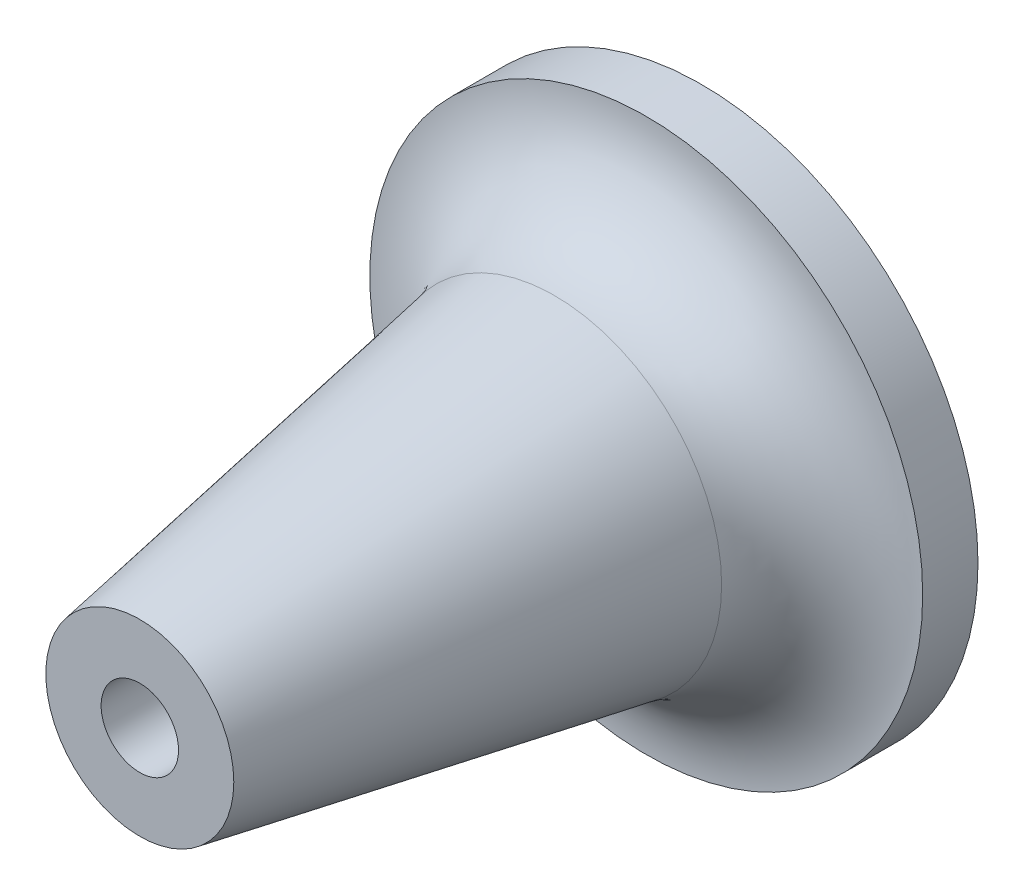
SolidWorks part; units mm, degrees
material "ABS"
ref_plane "Front Plane" through (0, 0, 0) normal (0, 0, 1) x (1, 0, 0)
ref_plane "Top Plane" through (0, 0, 0) normal (0, 1, 0) x (1, 0, 0)
ref_plane "Right Plane" through (0, 0, 0) normal (1, 0, 0) x (0, 0, -1)
sketch "Sketch1" plane through (0, 0, 0) normal (1, 0, 0) x (0, 0, -1)
  line L0 (-51.4955, 0) -> (51.4955, 0) construction
  line L1 (-33.7154, 3.5) -> (8.0846, 3.5)
  line L2 (-33.7154, 8.5) -> (3.7884, 15.1129)
  line L3 (12.0846, 25) -> (17.0846, 25)
  line L4 (8.0846, 0) -> (8.2846, 0)
  line L5 (-33.7154, 8.5) -> (-33.7154, 3.5)
  line L6 (8.2846, 11.55) -> (17.0846, 11.55)
  line L7 (17.0846, 11.55) -> (17.0846, 25)
  line L8 (8.2846, 0) -> (8.2846, 11.55)
  line L9 (8.0846, 3.5) -> (8.0846, 0)
  arc A0 (3.7884, 15.1129) -> (12.0846, 25) centre (2.045, 25) ccw
  dimension "D3" = 5
  dimension "D4" = 25
  dimension "D1" = 11.55
  dimension "D2" = 5
  dimension "D5" = 0.2
  dimension "D6" = 41.8
  dimension "D7" = 8.8
revolve "Revolve1" add sketch "Sketch1" angle 360 about L0
